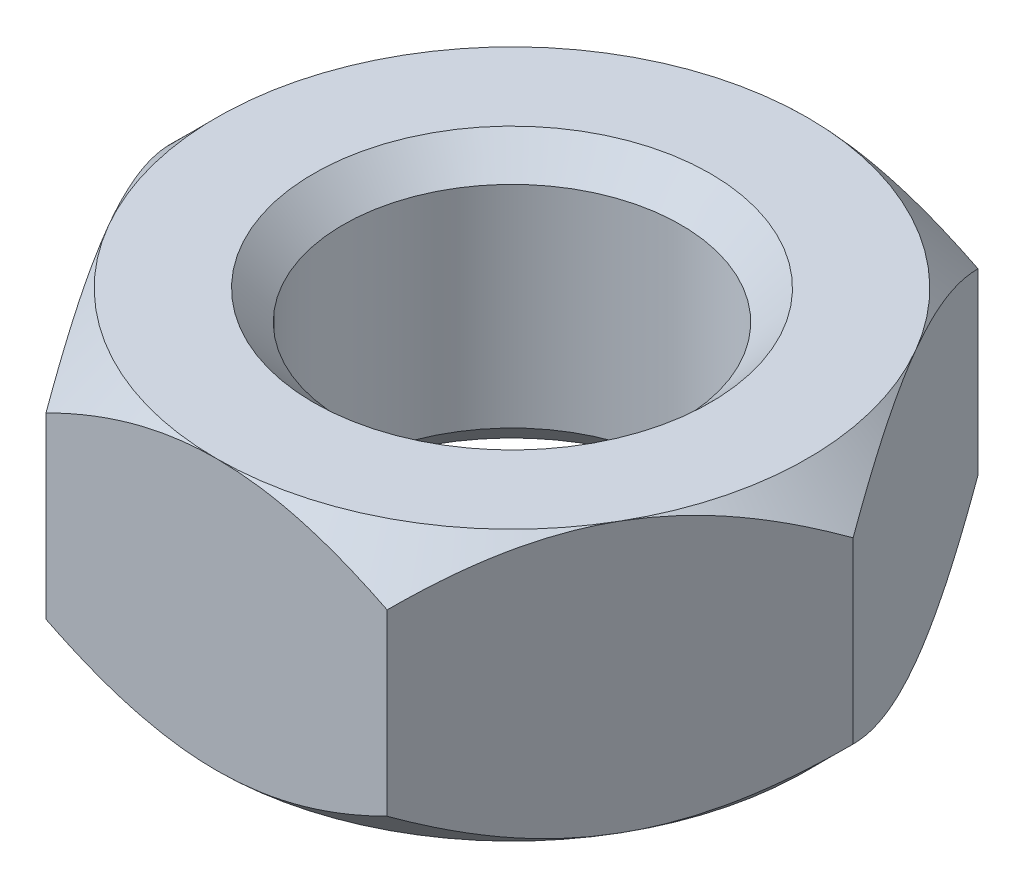
SolidWorks part; units mm, degrees
material "Cast Stainless Steel"
ref_plane "Front Plane" through (0, 0, 0) normal (0, 0, 1) x (1, 0, 0)
ref_plane "Top Plane" through (0, 0, 0) normal (0, 1, 0) x (1, 0, 0)
ref_plane "Right Plane" through (0, 0, 0) normal (1, 0, 0) x (0, 0, -1)
sketch "Sketch1" plane through (0, 0, 0) normal (0, 1, 0) x (1, 0, 0)
  line L0 (-4.0415, 0) -> (4.0415, 0) construction
  line L1 (4.0415, 0) -> (2.0207, 3.5)
  line L2 (2.0207, 3.5) -> (-2.0207, 3.5)
  line L3 (-2.0207, 3.5) -> (-4.0415, 0)
  line L4 (-4.0415, 0) -> (-2.0207, -3.5)
  line L5 (-2.0207, -3.5) -> (2.0207, -3.5)
  line L6 (2.0207, -3.5) -> (4.0415, 0)
  circle A0 centre (0, 0) radius 3.5 construction
  circle A1 centre (0, 0) radius 2
  point P12 (0, 0)
  dimension "D1" = 4
  dimension "D2" = 7
extrude "Boss-Extrude1" add sketch "Sketch1" along normal blind 3.2
sketch "Sketch3" plane through (0, 0, 0) normal (1, 0, 0) x (0, 0, -1)
  line L0 (-3.5, 0) -> (-4.1, 0.6)
  line L1 (-4.1, 0.6) -> (-4.1, 0)
  line L2 (-4.1, 0) -> (-3.5, 0)
  line L4 (-3.5, 1.6) -> (3.5, 1.6) construction
  line L6 (3.5, 3.2) -> (3.5, 0) construction
  line L7 (-4.1, 3.2) -> (-3.5, 3.2)
  line L8 (-4.1, 2.6) -> (-4.1, 3.2)
  line L9 (-3.5, 3.2) -> (-4.1, 2.6)
  line L10 (0, 0) -> (0, 3.2) construction
  line L12 (-3.5, 3.2) -> (-3.5, 0) construction
  point P7 (0, 1.6)
  dimension "D1" = 1.6
  dimension "D2" = 45
  dimension "D3" = 0.6
revolve "Cut-Revolve1" cut sketch "Sketch3" angle 360 about L10
chamfer "Chamfer1" distance 0.35 angle 45 2 edges at (0, 0, 2) (0, 3.2, 2)
equation "\"d\"= 4"
equation "\"m\"= 3.2"
equation "\"s\"= 7"
equation "\"e\"= 7.66"
equation "\"D1@Sketch1\"=\"d\""
equation "\"D2@Sketch1\"=\"s\""
equation "\"D1@Boss-Extrude1\"=\"m\""
equation "\"D1@Sketch3\"=\"m\"/2"
equation "\"D3@Sketch3\"=\"D1@Sketch3\"-1"
equation "\"D1@Chamfer1\"=\"s\"/20"
